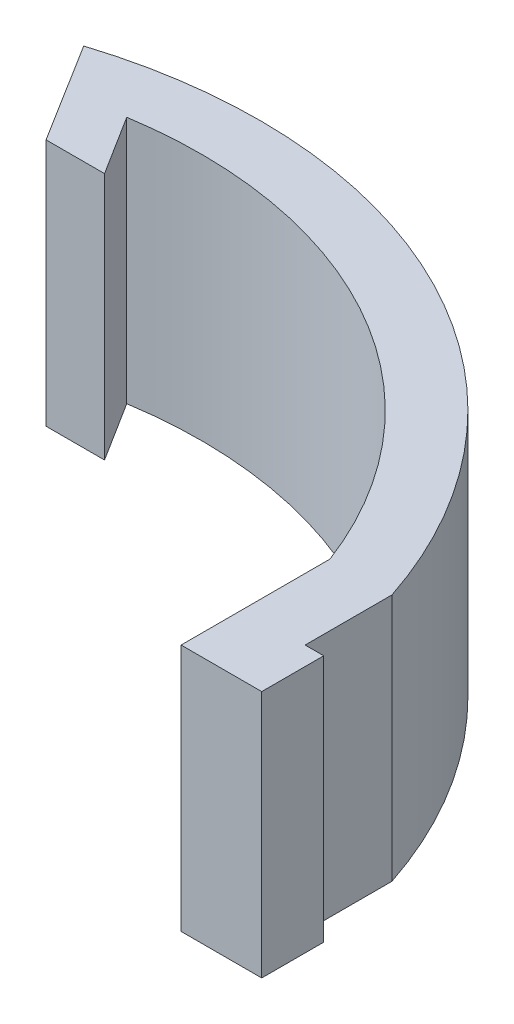
SolidWorks part; units mm, degrees
ref_plane "Front Plane" through (0, 0, 0) normal (0, 0, 1) x (1, 0, 0)
ref_plane "Top Plane" through (0, 0, 0) normal (0, 1, 0) x (1, 0, 0)
ref_plane "Right Plane" through (0, 0, 0) normal (1, 0, 0) x (0, 0, -1)
sketch "Sketch1" plane through (0, 0, 0) normal (0, 1, 0) x (1, 0, 0)
  line L0 (10.0718, -10.0822) -> (10.0718, -4.0822)
  line L1 (-9.4493, 7.248) -> (-7.93, 4.8335)
  line L2 (-7.93, 4.8335) -> (-10.2876, 4.8335)
  line L3 (-10.2876, 4.8335) -> (-12.8057, 8.8683)
  line L4 (10.0718, -10.0822) -> (12.5718, -10.0822)
  line L5 (12.5718, -4.0822) -> (12.5718, -7.5822)
  line L6 (12.5718, -10.0822) -> (13.3218, -10.0822)
  line L7 (12.5718, -7.5822) -> (13.3218, -7.5822)
  line L8 (13.3218, -10.0822) -> (13.3218, -7.5822)
  arc A0 (12.5718, -4.0822) -> (-12.8057, 8.8683) centre (-6.6579, -10.4244) ccw
  arc A1 (10.0718, -4.0822) -> (-9.4493, 7.248) centre (-6.6579, -10.4244) ccw
  dimension "D1" = 0.75
  dimension "D2" = 2.5
extrude "Boss-Extrude1" add sketch "Sketch1" along normal blind 10
